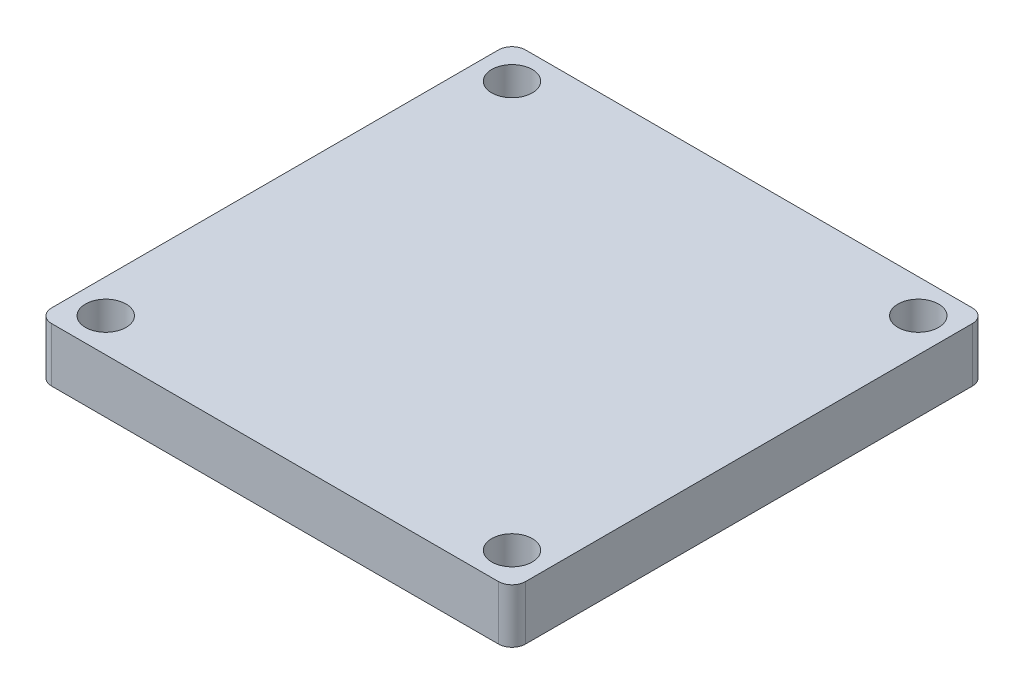
SolidWorks part; units mm, degrees
ref_plane "Front Plane" through (0, 0, 0) normal (0, 0, 1) x (1, 0, 0)
ref_plane "Top Plane" through (0, 0, 0) normal (0, 1, 0) x (1, 0, 0)
ref_plane "Right Plane" through (0, 0, 0) normal (1, 0, 0) x (0, 0, -1)
sketch "Sketch1" plane through (0, 0, 0) normal (0, 1, 0) x (1, 0, 0)
  line L1 (-17.5, -17.5) -> (17.5, -17.5)
  line L2 (-17.5, -17.5) -> (-17.5, 17.5)
  line L3 (-17.5, 17.5) -> (17.5, 17.5)
  line L4 (17.5, -17.5) -> (17.5, 17.5)
  line L5 (-17.5, -17.5) -> (17.5, 17.5) construction
  line L6 (-17.5, 17.5) -> (17.5, -17.5) construction
  line L7 (-15, 15) -> (15, 15) construction
  line L8 (-15, 15) -> (-15, -15) construction
  line L9 (-15, -15) -> (15, -15) construction
  line L10 (15, 15) -> (15, -15) construction
  line L11 (-15, 15) -> (15, -15) construction
  line L12 (-15, -15) -> (15, 15) construction
  circle A0 centre (-15, 15) radius 1.5
  circle A1 centre (15, 15) radius 1.5
  circle A2 centre (-15, -15) radius 1.5
  circle A3 centre (15, -15) radius 1.5
  point P0 (0, 0)
  point P6 (0, 0)
  dimension "D5" = 3
  dimension "D1" = 35
  dimension "D2" = 35
  dimension "D3" = 30
  dimension "D4" = 30
  dimension "D6" = 2
  dimension "D7" = 2
extrude "Boss-Extrude1" add sketch "Sketch1" along normal blind 4
fillet "Fillet3" radius 1 4 edges at (17.5, 2, 17.5) (17.5, 2, -17.5) (-17.5, 2, 17.5) (-17.5, 2, -17.5)
